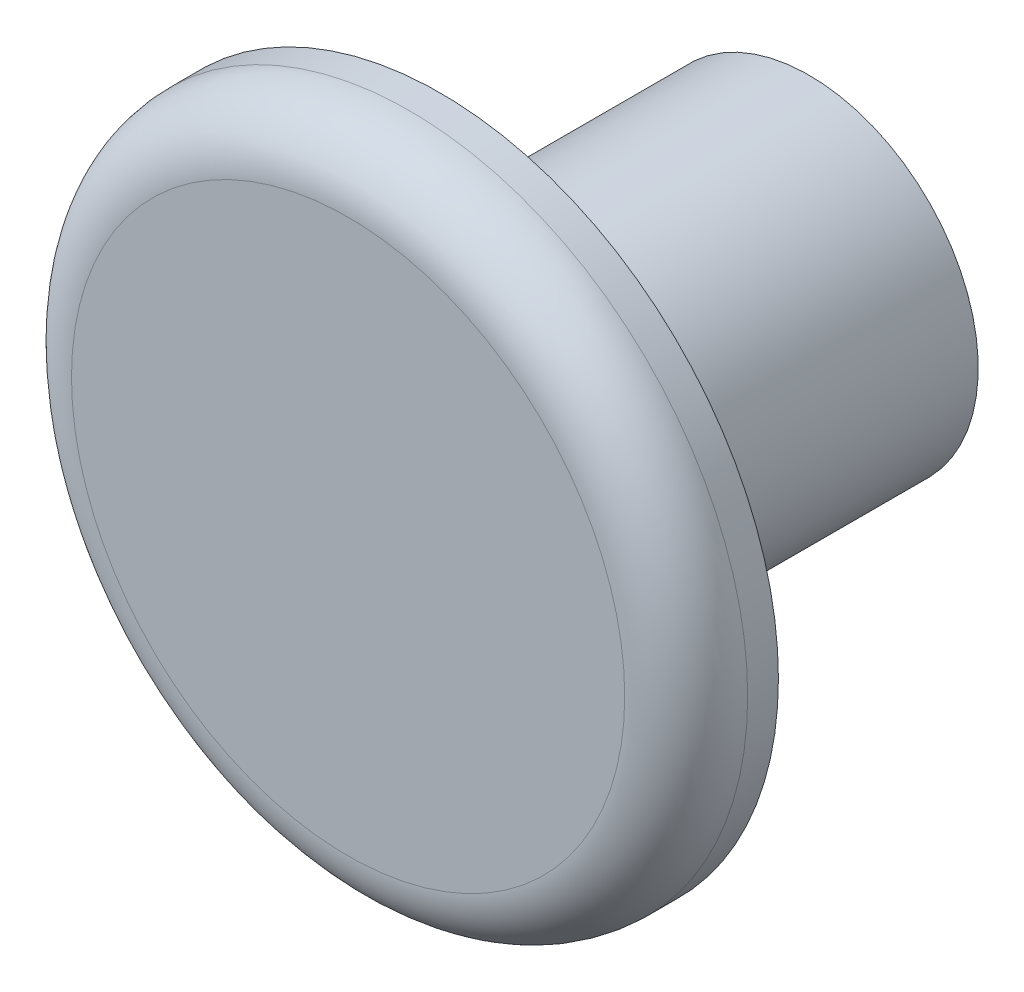
SolidWorks part; units mm, degrees
ref_plane "Front Plane" through (0, 0, 0) normal (1, 0, 0) x (0, 1, 0)
ref_plane "Top Plane" through (0, 0, 0) normal (0, 0, 1) x (0, 1, 0)
ref_plane "Right Plane" through (0, 0, 0) normal (0, 1, 0) x (-1, 0, 0)
sketch "Sketch1" plane through (0, 0, 0) normal (1, 0, 0) x (0, 1, 0)
  line L0 (0, 0) -> (18253.6496, 0) construction
  line L1 (0, 0) -> (0, 18253.6496) construction
  line L2 (0, -12) -> (-5.5, -12)
  line L3 (-5.5, -12) -> (-5.5, 0)
  line L4 (-5.5, 0) -> (-11, 0)
  line L5 (-11, 0) -> (-11, 3)
  line L6 (-11, 3) -> (0, 3)
  line L7 (0, 3) -> (0, -12)
  dimension "D1" = 22
  dimension "D2" = 11
  dimension "D3" = 15
  dimension "D4" = 12
revolve "Revolve1" add sketch "Sketch1" angle 360 about L1
fillet "Fillet1" radius 2 1 edges at (-11, 0, 3)
